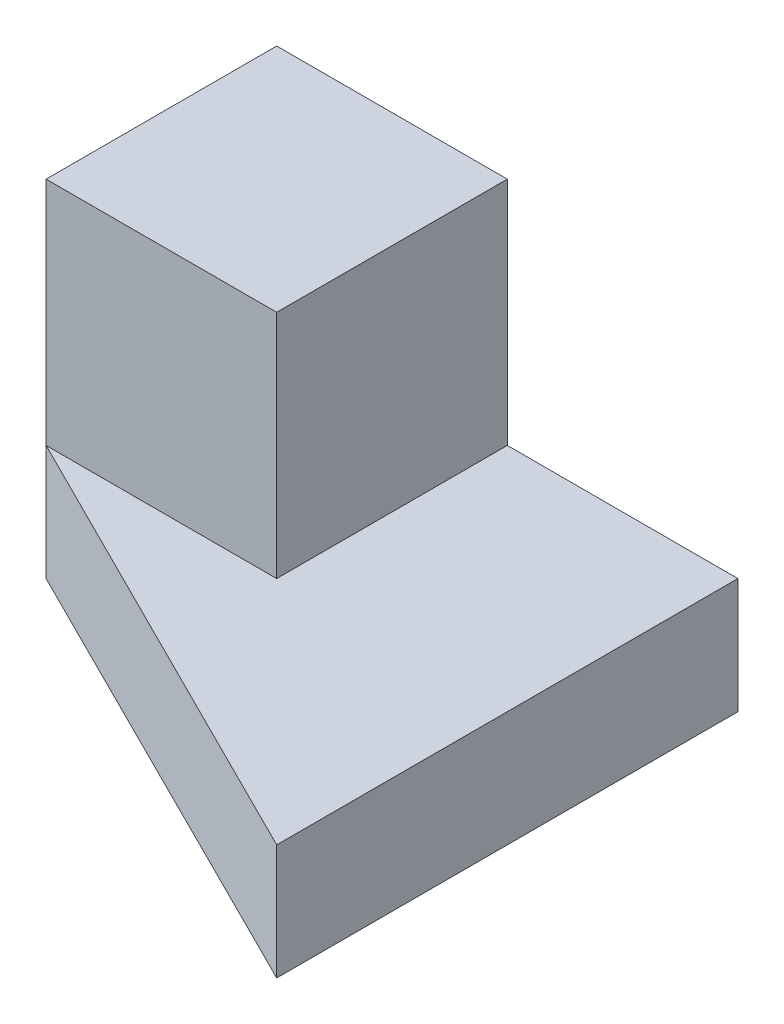
SolidWorks part; units mm, degrees
ref_plane "前基準面" through (0, 0, 0) normal (0, 0, 1) x (1, 0, 0)
ref_plane "上基準面" through (0, 0, 0) normal (0, 1, 0) x (1, 0, 0)
ref_plane "右基準面" through (0, 0, 0) normal (1, 0, 0) x (0, 0, -1)
sketch "草圖1" plane through (0, 0, 0) normal (0, 1, 0) x (1, 0, 0)
  line L0 (0, -10) -> (20, -20)
  line L1 (0, 0) -> (20, 0)
  line L2 (0, 0) -> (0, -10)
  line L4 (20, 0) -> (20, -20)
  dimension "D1" = 20
  dimension "D2" = 10
  dimension "D3" = 20
extrude "填料-伸長1" add sketch "草圖1" along normal blind 5
sketch "草圖2" plane through (0, 5, 0) normal (0, 1, 0) x (1, 0, 0)
  line L1 (0, 0) -> (10, 0)
  line L2 (0, 0) -> (0, -10)
  line L3 (0, -10) -> (10, -10)
  line L4 (10, 0) -> (10, -10)
  dimension "D1" = 10
  dimension "D2" = 10
extrude "填料-伸長2" add sketch "草圖2" along normal blind 10
